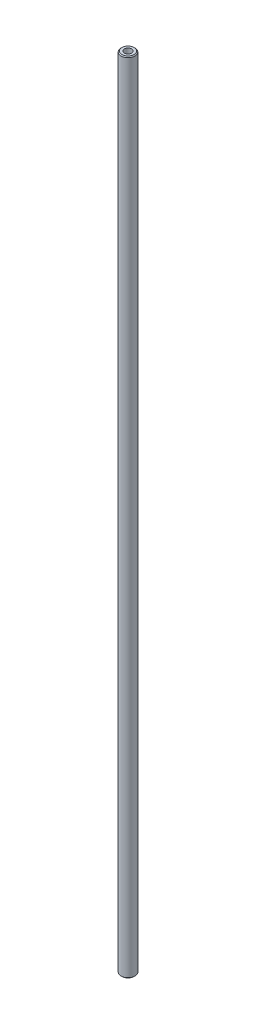
SolidWorks part; units mm, degrees
material "AISI 1020"
ref_plane "Plano frontal" through (0, 0, 0) normal (0, 0, 1) x (1, 0, 0)
ref_plane "Plano superior" through (0, 0, 0) normal (0, 1, 0) x (1, 0, 0)
ref_plane "Plano direito" through (0, 0, 0) normal (1, 0, 0) x (0, 0, -1)
sketch "Esboço3" plane through (0, 0, 0) normal (0, 1, 0) x (1, 0, 0)
  circle A0 centre (0, 0) radius 4
  dimension "D1" = 8
extrude "Ressalto-extrusão1" add sketch "Esboço3" along normal mid plane 459
chamfer "Chanfro1" distance 0.5 angle 45 2 edges at (0, -229.5, 4) (0, 229.5, 4)
hole_wizard "Furo roscado de M51" positions "Esboço5" profile "Esboço4" tap size "M5" standard "DIN"
sketch "Esboço5" plane through (0, 229.5, 0) normal (0, 1, 0) x (1, 0, 0)
  circle A0 centre (0, 0) radius 3.5 construction
  point P0 (0, 0)
sketch "Esboço4" plane through (0, 229.5, 0) normal (1, 0, 0) x (0, 0, 1)
  line L0 (0, 0) -> (0, 25.2618)
  line L1 (0, 25.2618) -> (2.1, 24)
  line L2 (2.1, 24) -> (2.1, 0)
  line L5 (2.1, 0) -> (0, 0)
  line L10 (0, 25.2618) -> (-2.1, 24) construction
  line L11 (0, -6.35) -> (0, 107.95) construction
  dimension "Tap Drill Dia." = 4.2
  dimension "Tap Drill Depth" = 24
  dimension "Drill Angle" = 118
cosmetic thread "Rosca de furo1" parameters "D1"=12, "D2"=5
mirror "Espelhar1" about plane through (0, 0, 0) normal (0, 1, 0) of "Furo roscado de M51"
